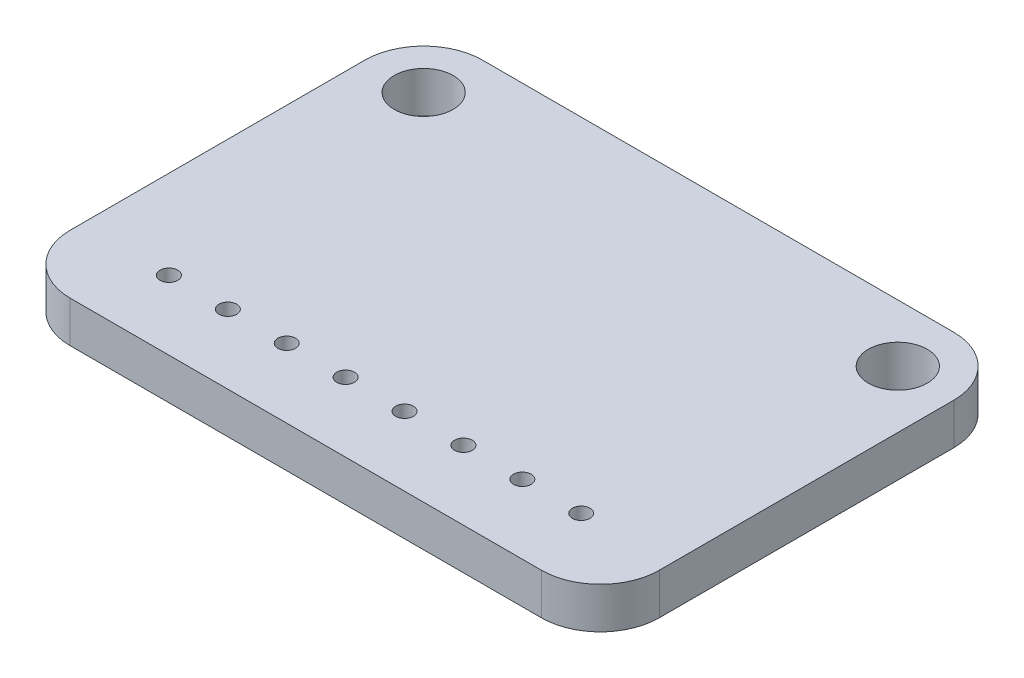
SolidWorks part; units mm, degrees
ref_plane "Front Plane" through (0, 0, 0) normal (0, 0, 1) x (1, 0, 0)
ref_plane "Top Plane" through (0, 0, 0) normal (0, 1, 0) x (1, 0, 0)
ref_plane "Right Plane" through (0, 0, 0) normal (1, 0, 0) x (0, 0, -1)
sketch "Sketch1" plane through (0, 0, 0) normal (0, 1, 0) x (1, 0, 0)
  line L1 (10.16, 8.89) -> (-10.16, 8.89)
  line L2 (12.7, 6.35) -> (12.7, -6.35)
  line L3 (10.16, -8.89) -> (-10.16, -8.89)
  line L4 (-12.7, 6.35) -> (-12.7, -6.35)
  line L5 (12.7, 8.89) -> (-12.7, -8.89) construction
  line L6 (12.7, -8.89) -> (-12.7, 8.89) construction
  line L14 (0, 0) -> (0, 10.4198) construction
  line L15 (-10.16, 6.35) -> (10.16, -6.35) construction
  line L16 (10.16, 6.35) -> (-10.16, -6.35) construction
  line L17 (0, 0) -> (-8.3012, 0) construction
  arc A0 (10.16, 8.89) -> (12.7, 6.35) centre (10.16, 6.35) cw
  arc A1 (12.7, -6.35) -> (10.16, -8.89) centre (10.16, -6.35) cw
  arc A2 (-10.16, -8.89) -> (-12.7, -6.35) centre (-10.16, -6.35) cw
  arc A3 (-10.16, 8.89) -> (-12.7, 6.35) centre (-10.16, 6.35) ccw
  circle A8 centre (-10.2235, 6.4135) radius 1.27
  circle A9 centre (10.2235, 6.4135) radius 1.27
  point P0 (0, 0)
  point P18 (0, 0)
  point P36 (0, 0)
  dimension "D1" = 2.54
  dimension "D9" = 2.54
  dimension "D4" = 20.447
  dimension "D2" = 17.78
  dimension "D3" = 25.4
  dimension "D5" = 2.4765
extrude "Boss-Extrude1" add sketch "Sketch1" along normal blind 1.778
sketch "Sketch2" plane through (0, 0, 0) normal (0, -1, 0) x (1, 0, 0)
  line L0 (-10.16, 8.89) -> (10.16, 8.89) construction
  line L1 (-6.604, 7.239) -> (6.604, 7.239)
  line L2 (-6.604, 7.239) -> (-6.604, 4.572)
  line L3 (-6.604, 4.572) -> (6.604, 4.572)
  line L4 (6.604, 7.239) -> (6.604, 4.572)
  line L5 (0, 0) -> (0, 2.4773) construction
  point P9 (0, 0)
  dimension "D1" = 13.208
  dimension "D2" = 2.667
  dimension "D3" = 1.651
extrude "Boss-Extrude2" add sketch "Sketch2" along normal blind 2.159
sketch "Sketch3" plane through (0, -2.159, 0) normal (0, -1, 0) x (1, 0, 0)
  line L0 (-6.604, 5.9055) -> (6.604, 5.9055) construction
  line L1 (-6.604, 7.239) -> (-6.604, 4.572) construction
  line L2 (6.604, 4.572) -> (6.604, 7.239) construction
  line L3 (0, 0) -> (0, 11.811) construction
  circle A0 centre (-8.89, 5.9055) radius 0.381
  circle A1 centre (-6.35, 5.9055) radius 0.381
  circle A2 centre (-3.81, 5.9055) radius 0.381
  circle A3 centre (6.35, 5.9055) radius 0.381
  circle A4 centre (8.89, 5.9055) radius 0.381
  circle A5 centre (-1.27, 5.9055) radius 0.381
  circle A6 centre (1.27, 5.9055) radius 0.381
  circle A7 centre (3.81, 5.9055) radius 0.381
  point P23 (0, 0)
  point P26 (0, 0)
  dimension "D2" = 2.54
  dimension "D3" = 0.762
  dimension "D1" = 2.54
  dimension "D4" = 2.54
  dimension "D5" = 2.54
extrude "Cut-Extrude1" cut sketch "Sketch3" against normal through all
sketch "Sketch4" plane through (-12.7, 0, 0) normal (-1, 0, 0) x (0, 0, 1)
  line L0 (-6.35, 0) -> (6.35, 0) construction
  line L1 (3.3678, 0) -> (8.4788, 0)
  line L2 (3.3678, 0) -> (3.3678, -3.1476)
  line L3 (3.3678, -3.1476) -> (8.4788, -3.1476)
  line L4 (8.4788, 0) -> (8.4788, -3.1476)
extrude "Cut-Extrude2" cut sketch "Sketch4" against normal through all
sketch "Sketch5" plane through (0, 0, 0) normal (0, -1, 0) x (1, 0, 0)
  text T0 "BMP390\r\n"
  point P1 (-5.8803, -4.4852)
  point P2 (-6.2454, -7.5883)
extrude "Cut-Extrude3" cut sketch "Sketch5" against normal blind 0.0254
